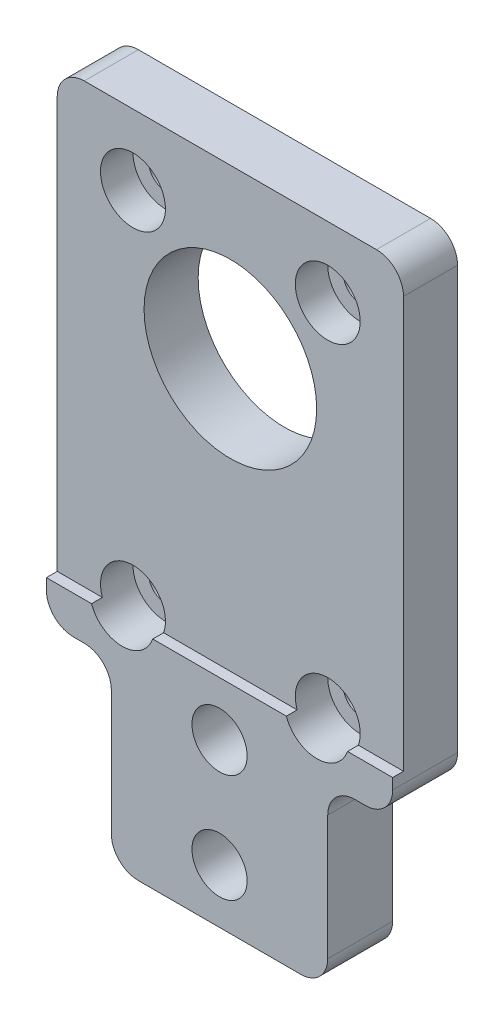
SolidWorks part; units mm, degrees
ref_plane "Front Plane" through (0, 0, 0) normal (0, 0, 1) x (1, 0, 0)
ref_plane "Top Plane" through (0, 0, 0) normal (0, 1, 0) x (1, 0, 0)
ref_plane "Right Plane" through (0, 0, 0) normal (1, 0, 0) x (0, 0, -1)
sketch "Sketch1" plane through (0, 0, 0) normal (0, 0, 1) x (1, 0, 0)
  line L0 (0, -353.8104) -> (0, 17336.7087) construction
  line L1 (-10, -15) -> (-10, 15)
  line L2 (-10, 15) -> (-15, 30)
  line L3 (10, -15) -> (-10, -15)
  line L4 (10, -15) -> (10, 15)
  line L5 (10, 15) -> (15, 30)
  arc A0 (15, 30) -> (-15, 30) centre (0, 30) ccw
  circle A1 centre (0, 0) radius 2.55
  circle A2 centre (0, -10) radius 2.55
  dimension "D1" = 5.1
  dimension "D2" = 5.1
  dimension "D3" = 10
  dimension "D4" = 30
  dimension "D5" = 30
  dimension "D7" = 30
  dimension "D6" = 5
  dimension "D8" = 20
  dimension "D9" = 10
  dimension "D10" = 30
extrude "Boss-Extrude2" add sketch "Sketch1" along normal blind 6
sketch "Sketch7" plane through (0, 0, 0) normal (0, 0, -1) x (-1, 0, 0)
  line L0 (0, -970) -> (0, 49030) construction
  line L1 (-16, 45.5) -> (16, 45.5)
  line L2 (-16, 45.5) -> (-16, 1.5)
  line L3 (-16, 1.5) -> (16, 1.5)
  line L4 (16, 45.5) -> (16, 1.5)
  arc A0 (15, 30) -> (-15, 30) centre (0, 30) ccw construction
  dimension "D1" = 32
  dimension "D2" = 44
  dimension "D3" = 16
  dimension "D4" = 15.5
extrude "Boss-Extrude3" add sketch "Sketch7" against normal blind 6
fillet "Fillet1" radius 2.5 8 edges at (10, -15, 3) (-10, -15, 3) (16, 45.5, 3) (10, 1.5, 3) (16, 1.5, 3) (-16, 45.5, 3) (-16, 1.5, 3) (-10, 1.5, 3)
sketch "Sketch3" plane through (0, 0, 6) normal (0, 0, 1) x (1, 0, 0)
  circle A0 centre (0, 30) radius 7.975
  dimension "D1" = 15.95
  dimension "D2" = 30
extrude "Cut-Extrude2" cut sketch "Sketch3" against normal through all
sketch "Sketch2" plane through (0, 0, 6) normal (0, 0, 1) x (1, 0, 0)
  line L0 (-1009.4328, 39) -> (48990.5672, 39) construction
  line L1 (-1007.6541, 6) -> (48992.3459, 6) construction
  line L2 (-9, -973.06) -> (-9, 49026.94) construction
  line L3 (9, -977.0128) -> (9, 49022.9872) construction
  line L4 (0, -970) -> (0, 49030) construction
  line L5 (-1000, 30) -> (49000, 30) construction
  line L6 (-13.5, 45.5) -> (13.5, 45.5) construction
  circle A0 centre (-9, 39) radius 1.55
  circle A1 centre (9, 39) radius 1.55
  circle A2 centre (9, 6) radius 1.55
  circle A3 centre (-9, 6) radius 1.55
  dimension "D3" = 6.5
  dimension "D4" = 33
  dimension "D5" = 3.1
  dimension "D6" = 3.1
  dimension "D7" = 3.1
  dimension "D8" = 3.1
  dimension "D1" = 9
  dimension "D2" = 9
extrude "Cut-Extrude1" cut sketch "Sketch2" against normal through all
sketch "Sketch6" plane through (0, 0, 6) normal (0, 0, 1) x (1, 0, 0)
  line L0 (-7.5, -15) -> (7.5, -15) construction
  line L1 (-30, 5) -> (30, 5)
  line L2 (-30, 5) -> (-30, 55)
  line L3 (-30, 55) -> (30, 55)
  line L4 (30, 5) -> (30, 55)
  line L5 (-30, 5) -> (30, 55) construction
  line L6 (-30, 55) -> (30, 5) construction
  point P0 (0, 30)
  dimension "D1" = 20
  dimension "D2" = 60
extrude "Cut-Extrude5" cut sketch "Sketch6" against normal blind 1
sketch "Sketch8" plane through (0, 0, 6) normal (0, 0, 1) x (1, 0, 0)
  circle A0 centre (-9, 39) radius 3
  circle A1 centre (9, 39) radius 3
  circle A2 centre (9, 6) radius 3
  circle A3 centre (-9, 6) radius 3
  dimension "D1" = 6
  dimension "D2" = 6
  dimension "D3" = 6
  dimension "D4" = 6
extrude "Cut-Extrude6" cut sketch "Sketch8" against normal blind 4
sketch "Sketch9" plane through (0, 0, 6) normal (0, 0, 1) x (1, 0, 0)
  circle A0 centre (0, -10) radius 2.55
  circle A1 centre (0, 0) radius 2.55
  dimension "D1" = 5.1
  dimension "D2" = 5.1
extrude "Cut-Extrude7" cut sketch "Sketch9" against normal through all
